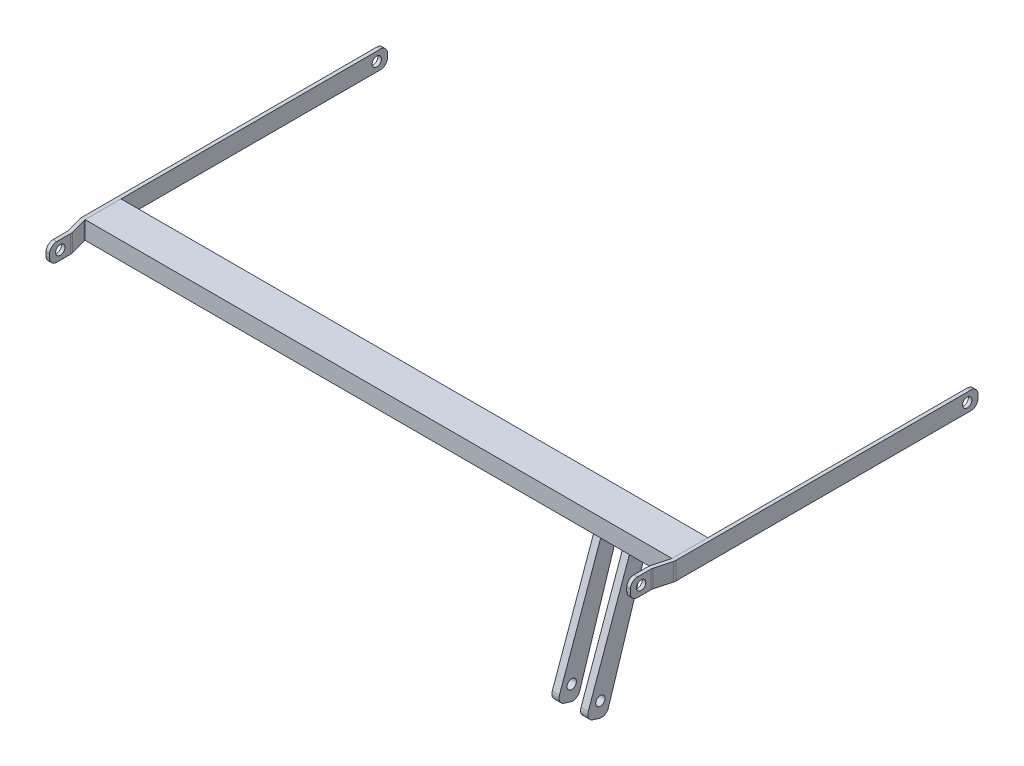
SolidWorks part; units mm, degrees
ref_plane "Front Plane" through (0, 0, 0) normal (0, 0, 1) x (1, 0, 0)
ref_plane "Top Plane" through (0, 0, 0) normal (0, 1, 0) x (1, 0, 0)
ref_plane "Right Plane" through (0, 0, 0) normal (1, 0, 0) x (0, 0, -1)
ref_plane "Plane1" through (400, 0, 0) normal (1, 0, 0) x (0, 0, -1)
sketch "Sketch1" plane through (0, 0, 0) normal (0, 1, 0) x (1, 0, 0)
  line L0 (413.51, 0) -> (413.51, -420.6583)
  line L1 (413.1693, -423.2465) -> (407.0848, -445.9539)
  line L2 (406.7441, -448.5421) -> (406.7441, -477.2256)
  line L3 (0, 229.7203) -> (0, -245.5471) construction
  line L4 (408.51, 0) -> (408.51, -420)
  line L5 (408.1693, -422.5882) -> (402.0848, -445.2957)
  line L6 (401.7441, -447.8839) -> (401.7441, -477.2256)
  line L7 (413.51, 0) -> (408.51, 0)
  line L8 (406.7441, -477.2256) -> (401.7441, -477.2256)
  line L9 (408.51, 0) -> (408.51, -421.3165) construction
  line L10 (408.51, -421.3165) -> (401.7441, -446.5674) construction
  line L11 (401.7441, -446.5674) -> (401.7441, -477.2256) construction
  line L12 (413.51, -421.9748) -> (406.7441, -447.2256) construction
  line L13 (406.7441, -447.2256) -> (406.7441, -477.2256) construction
  line L14 (413.51, 0) -> (413.51, -421.9748) construction
  line L15 (-406.7441, -477.2256) -> (-401.7441, -477.2256)
  line L16 (-413.51, 0) -> (-408.51, 0)
  line L17 (-401.7441, -447.8839) -> (-401.7441, -477.2256)
  line L18 (-408.1693, -422.5882) -> (-402.0848, -445.2957)
  line L19 (-408.51, 0) -> (-408.51, -420)
  line L20 (-406.7441, -448.5421) -> (-406.7441, -477.2256)
  line L21 (-413.1693, -423.2465) -> (-407.0848, -445.9539)
  line L22 (-413.51, 0) -> (-413.51, -420.6583)
  arc A0 (408.51, -420) -> (408.1693, -422.5882) centre (398.51, -420) cw
  arc A1 (402.0848, -445.2957) -> (401.7441, -447.8839) centre (411.7441, -447.8839) ccw
  arc A2 (407.0848, -445.9539) -> (406.7441, -448.5421) centre (416.7441, -448.5421) ccw
  arc A3 (413.51, -420.6583) -> (413.1693, -423.2465) centre (403.51, -420.6583) cw
  arc A4 (-413.51, -420.6583) -> (-413.1693, -423.2465) centre (-403.51, -420.6583) ccw
  arc A5 (-407.0848, -445.9539) -> (-406.7441, -448.5421) centre (-416.7441, -448.5421) cw
  arc A6 (-402.0848, -445.2957) -> (-401.7441, -447.8839) centre (-411.7441, -447.8839) cw
  arc A7 (-408.51, -420) -> (-408.1693, -422.5882) centre (-398.51, -420) ccw
  point P21 (406.7441, -447.2256)
  point P41 (-406.7441, -447.2256)
  dimension "D7" = 10
  dimension "D1" = 827.02
  dimension "D2" = 420
  dimension "D3" = 30
  dimension "D5" = 165
  dimension "D6" = 5
extrude "Boss-Extrude1" add sketch "Sketch1" along normal mid plane 25
fillet "Fillet1" radius 10 4 edges at (-404.2441, -12.5, 477.2256) (-404.2441, 12.5, 477.2256) (-411.01, -12.5, 0) (-411.01, 12.5, 0)
fillet "Fillet2" radius 10 4 edges at (404.2441, -12.5, 477.2256) (404.2441, 12.5, 477.2256) (411.01, -12.5, 0) (411.01, 12.5, 0)
sketch "Sketch2" plane through (413.51, 0, 0) normal (1, 0, 0) x (0, 0, -1)
  line L0 (-477.2256, 0) -> (-634.5027, 0) construction
  line L1 (-477.2256, 2.5) -> (-477.2256, -2.5) construction
  line L2 (0, 0) -> (-64.8709, 0) construction
  circle A0 centre (-462.2256, 0) radius 6.5
  circle A1 centre (-15, 0) radius 6.5
  dimension "D1" = 13
  dimension "D3" = 13
  dimension "D2" = 15
  dimension "D4" = 15
extrude "Cut-Extrude1" cut sketch "Sketch2" against normal blind 869
sketch "Sketch3" plane through (0, 12.5, 0) normal (0, 1, 0) x (1, 0, 0)
  line L0 (-413.51, -10) -> (-413.51, -420.6583) construction
  line L1 (-413.51, -45) -> (-408.51, -45)
  line L2 (-413.51, -45) -> (-413.51, -345)
  line L3 (-413.51, -345) -> (-408.51, -345)
  line L4 (413.51, -45) -> (413.51, -345)
  line L5 (413.51, -420.6583) -> (413.51, -10) construction
  line L6 (408.51, 0) -> (413.51, 0) construction
  line L7 (408.51, -345) -> (408.51, -45)
  line L8 (408.51, -10) -> (408.51, -420) construction
  line L9 (-408.51, -345) -> (-408.51, -45)
  line L10 (-408.51, -420) -> (-408.51, -10) construction
  line L11 (408.51, -345) -> (413.51, -345)
  line L12 (408.51, -45) -> (413.51, -45)
  dimension "D1" = 45
  dimension "D2" = 300
sketch "Sketch8" plane through (408.51, 0, 0) normal (-1, 0, 0) x (0, 0, 1)
  line L0 (10, 12.5) -> (420.6583, 12.5) construction
  line L1 (371.0504, 12.5) -> (421.0504, 12.5)
  line L2 (371.0504, 12.5) -> (371.0504, -12.5)
  line L3 (371.0504, -12.5) -> (421.0504, -12.5)
  line L4 (421.0504, 12.5) -> (421.0504, -12.5)
  line L5 (10, -12.5) -> (420.6583, -12.5) construction
  dimension "D1" = 50
extrude "Boss-Extrude2" add sketch "Sketch8" along normal up to next separate body
sketch "Sketch9" plane through (0, -12.5, 0) normal (0, -1, 0) x (1, 0, 0)
  line L0 (324.531, 421.0504) -> (324.531, 371.0504) construction
  line L1 (258.51, 416.0504) -> (358.51, 416.0504)
  line L2 (258.51, 416.0504) -> (258.51, 376.0504)
  line L3 (258.51, 376.0504) -> (358.51, 376.0504)
  line L4 (358.51, 416.0504) -> (358.51, 376.0504)
  line L5 (-408.4547, 421.0504) -> (408.51, 421.0504) construction
  line L6 (-408.51, 371.0504) -> (408.51, 371.0504) construction
  line L7 (240.5521, 396.0504) -> (408.51, 396.0504) construction
  line L8 (408.51, 10) -> (408.51, 420) construction
  line L9 (408.51, 371.0504) -> (408.51, 421.0504) construction
  point P14 (324.531, 396.0504)
  dimension "D1" = 40
  dimension "D2" = 100
  dimension "D3" = 50
extrude "Boss-Extrude3" add sketch "Sketch9" along normal blind 5 separate body
ref_plane "Plane2" through (313.51, 0, 0) normal (1, 0, 0) x (0, 0, -1)
sketch "Sketch22" plane through (313.51, 0, 0) normal (1, 0, 0) x (0, 0, -1)
  line L1 (-376.0504, -17.5) -> (-416.0504, -17.5) construction
  point P8 (-396.0504, -17.5)
  point P11 (-498.1162, -175.1147)
  point P14 (-521.7584, -156.6473)
  line B0 (-410.1143, -22.7162) -> (-381.9866, -12.2838)
  line B1 (-381.9866, -12.2838) -> (-439.5774, -193.3454)
  line B2 (-452.138, -199.8438) -> (-461.328, -196.9208)
  line B3 (-467.7145, -184.0284) -> (-410.1143, -22.7162)
  line B4 (-456.733, -198.3823) -> (-436.8321, -135.8152) construction
  arc B5 (-439.5774, -193.3454) -> (-452.138, -199.8438) centre (-449.1069, -190.3143) cw
  arc B6 (-461.328, -196.9208) -> (-467.7145, -184.0284) centre (-458.2969, -187.3912) cw
  circle B7 centre (-450.6708, -179.3232) radius 6.5
  dimension "D1" = 30
  dimension "D2" = 200
sketch_block_instance "Block1-1"
sketch_block "Block1" parameters "D2"=10, "D4"=13, "D1"=30, "D3"=20
ref_plane "Plane3" through (338.51, 0, 0) normal (1, 0, 0) x (0, 0, -1)
sketch "Sketch23" plane through (338.51, 0, 0) normal (1, 0, 0) x (0, 0, -1)
  line L0 (-410.1143, -22.7162) -> (-381.9866, -12.2838) construction
  line L1 (-381.9866, -12.2838) -> (-439.5774, -193.3454) construction
  line L2 (-452.138, -199.8438) -> (-461.328, -196.9208) construction
  line L3 (-467.7145, -184.0284) -> (-410.1143, -22.7162) construction
  line L4 (-410.1143, -22.7162) -> (-381.9866, -12.2838)
  line L5 (-381.9866, -12.2838) -> (-439.5774, -193.3454)
  line L6 (-452.138, -199.8438) -> (-461.328, -196.9208)
  line L7 (-467.7145, -184.0284) -> (-410.1143, -22.7162)
  arc A0 (-452.138, -199.8438) -> (-439.5774, -193.3454) centre (-449.1069, -190.3143) ccw construction
  circle A1 centre (-450.6708, -179.3232) radius 6.5 construction
  arc A2 (-467.7145, -184.0284) -> (-461.328, -196.9208) centre (-458.2969, -187.3912) ccw construction
  arc A3 (-452.138, -199.8438) -> (-439.5774, -193.3454) centre (-449.1069, -190.3143) ccw
  circle A4 centre (-450.6708, -179.3232) radius 6.5
  arc A5 (-467.7145, -184.0284) -> (-461.328, -196.9208) centre (-458.2969, -187.3912) ccw
extrude "Boss-Extrude4" add sketch "Sketch23" against normal blind 10
mirror "Mirror1" about plane through (313.51, 0, 0) normal (1, 0, 0) of "Boss-Extrude4"
sketch "Bend-Lines1" [suppressed] plane through (0, 0, 0) normal (0, 1, 0) x (1, 0, 0)
sketch "Bounding-Box1" [suppressed] plane through (0, 0, 0) normal (0, 1, 0) x (1, 0, 0)
